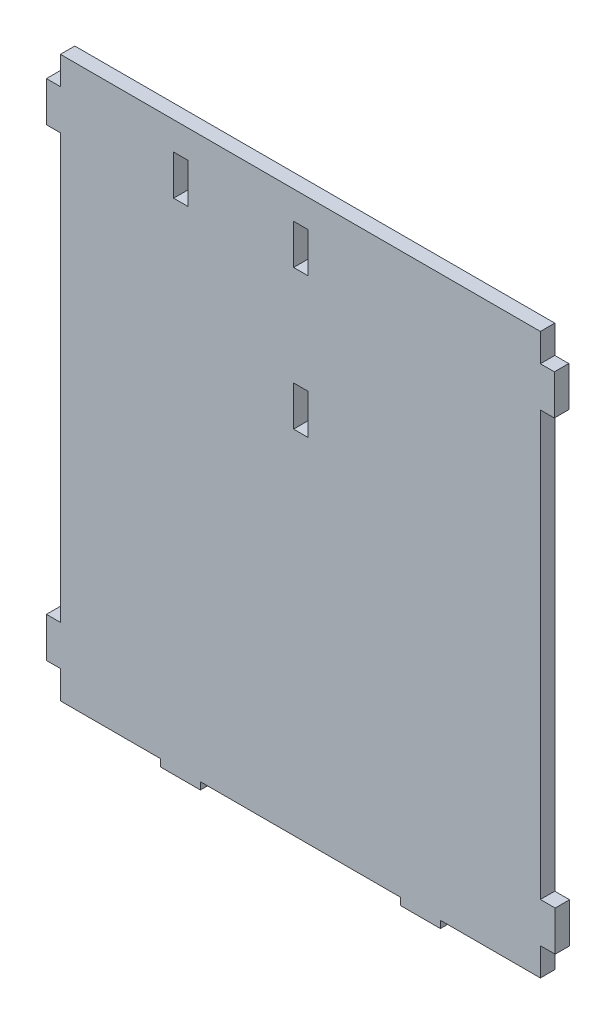
SolidWorks part; units mm, degrees
ref_plane "Front Plane" through (0, 0, 0) normal (0, 0, 1) x (1, 0, 0)
ref_plane "Top Plane" through (0, 0, 0) normal (0, 1, 0) x (1, 0, 0)
ref_plane "Right Plane" through (0, 0, 0) normal (1, 0, 0) x (0, 0, -1)
sketch "Sketch1" plane through (0, 0, 0) normal (0, 0, 1) x (1, 0, 0)
  line L0 (-0.5145, 322.5) -> (-0.5145, 175) construction
  line L1 (-300.5145, 322.5) -> (299.4855, 322.5)
  line L2 (-300.5145, 322.5) -> (-300.5145, 287.5)
  line L3 (-300.5145, -377.5) -> (-175.5145, -377.5)
  line L4 (299.4855, 322.5) -> (299.4855, 287.5)
  line L5 (-300.5145, -342.5) -> (-300.5145, -377.5)
  line L6 (-300.5145, 237.5) -> (-300.5145, -292.5)
  line L7 (299.4855, -342.5) -> (299.4855, -377.5)
  line L12 (299.4855, 237.5) -> (299.4855, -292.5)
  line L13 (-0.5145, 322.5) -> (-0.5145, -377.5) construction
  line L14 (174.4855, -377.5) -> (174.4855, -386.5)
  line L19 (-141, 237.5) -> (-159, 237.5)
  line L20 (-159, 287.5) -> (-159, 237.5)
  line L21 (174.4855, -386.5) -> (124.4855, -386.5)
  line L22 (-125.5145, -377.5) -> (124.4855, -377.5)
  line L23 (316.971, 237.5) -> (299.4855, 237.5)
  line L24 (-0.5145, 175) -> (9, 175) construction
  line L26 (-9, 287.5) -> (9, 287.5)
  line L27 (-9, 287.5) -> (-9, 237.5)
  line L28 (-9, 237.5) -> (9, 237.5)
  line L29 (9, 287.5) -> (9, 237.5)
  line L30 (-9, 287.5) -> (9, 237.5) construction
  line L31 (-9, 237.5) -> (9, 287.5) construction
  line L32 (-175.5145, -377.5) -> (-175.5145, -386.5)
  line L33 (-141, 287.5) -> (-159, 287.5)
  line L34 (-141, 287.5) -> (-141, 237.5)
  line L35 (-9, 112.5) -> (9, 112.5)
  line L36 (9, 62.5) -> (9, 112.5)
  line L37 (-9, 62.5) -> (9, 62.5)
  line L38 (-9, 62.5) -> (-9, 112.5)
  line L39 (-318, 287.5) -> (-300.5145, 287.5)
  line L40 (-318, 287.5) -> (-318, 237.5)
  line L41 (-318, 237.5) -> (-300.5145, 237.5)
  line L43 (-175.5145, -386.5) -> (-125.5145, -386.5)
  line L44 (-125.5145, -377.5) -> (-125.5145, -386.5)
  line L46 (316.971, 287.5) -> (299.4855, 287.5)
  line L47 (316.971, 287.5) -> (316.971, 237.5)
  line L48 (318, -342.5) -> (318, -292.5)
  line L49 (318, -342.5) -> (299.4855, -342.5)
  line L51 (318, -292.5) -> (299.4855, -292.5)
  line L52 (-318, -292.5) -> (-300.5145, -292.5)
  line L54 (-318, -342.5) -> (-300.5145, -342.5)
  line L55 (-318, -342.5) -> (-318, -292.5)
  line L56 (124.4855, -377.5) -> (124.4855, -386.5)
  line L57 (174.4855, -377.5) -> (299.4855, -377.5)
  point P0 (0, 0)
  point P8 (-0.5145, 175)
  dimension "D1" = 700
  dimension "D2" = 600
  dimension "D3" = 50
  dimension "D4" = 35
  dimension "D5" = 18
  dimension "D6" = 50
  dimension "D7" = 50
  dimension "D8" = 35
  dimension "D9" = 35
  dimension "D10" = 700
  dimension "D11" = 35
  dimension "D12" = 50
extrude "Boss-Extrude1" add sketch "Sketch1" along normal blind 18
